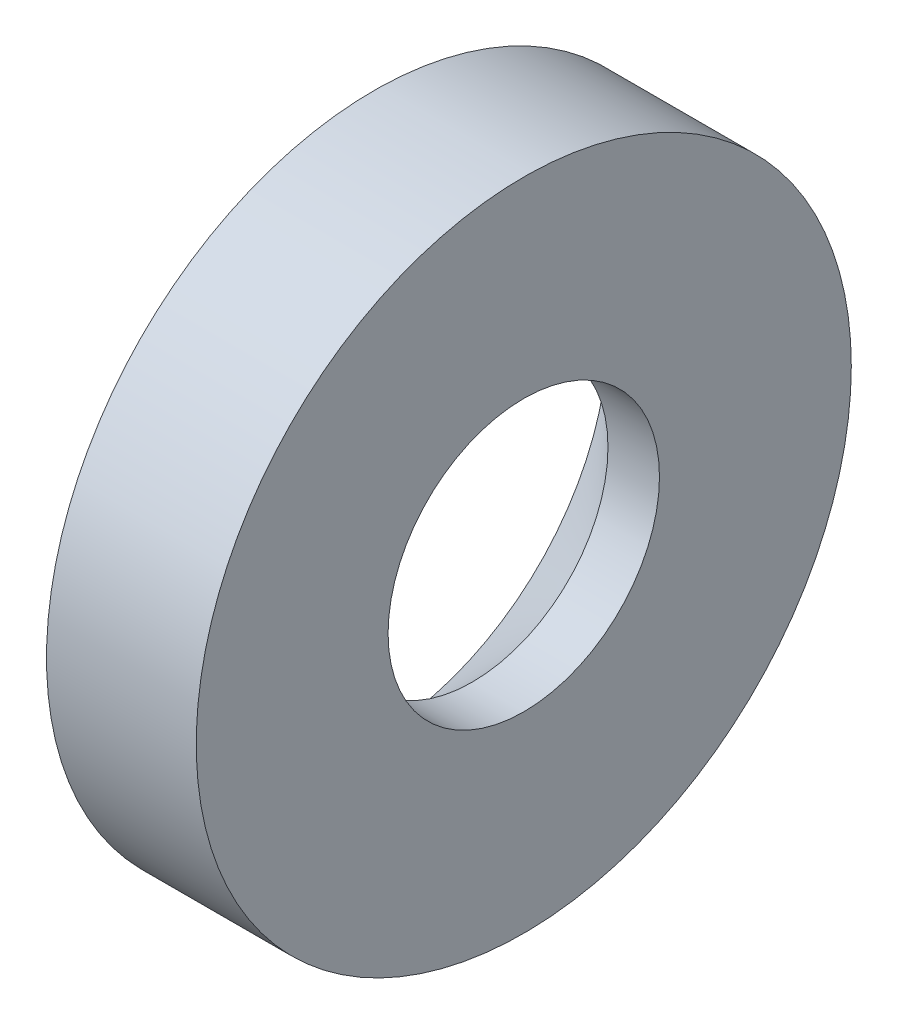
SolidWorks part; units mm, degrees
ref_plane "Front Plane" through (0, 0, 0) normal (0, 0, 1) x (1, 0, 0)
ref_plane "Top Plane" through (0, 0, 0) normal (0, 1, 0) x (1, 0, 0)
ref_plane "Right Plane" through (0, 0, 0) normal (1, 0, 0) x (0, 0, -1)
sketch "Sketch1" plane through (0, 0, 0) normal (1, 0, 0) x (0, 0, -1)
  circle A0 centre (0, 0) radius 17.5
  dimension "D1" = 35
extrude "Boss-Extrude1" add sketch "Sketch1" along normal mid plane 8
hole_wizard "CSK for M20 SFHCS1" positions "Sketch7" profile "Sketch6" countersink size "M20" standard "ANSI Metric"
sketch "Sketch7" plane through (-4, 0, 0) normal (-1, 0, 0) x (0, 0, 1)
  point P0 (0, 0)
sketch "Sketch6" plane through (-4, 0, 0) normal (0, 1, 0) x (0, 0, 1)
  line L0 (0, 0) -> (0, 35)
  line L1 (0, 35) -> (7.25, 30.6438)
  line L2 (7.25, 30.6438) -> (7.25, 5.25)
  line L3 (7.25, 5.25) -> (12.5, 0)
  line L5 (12.5, 0) -> (0, 0)
  line L6 (-7.25, 5.25) -> (-12.5, 0) construction
  line L10 (0, 35) -> (-7.25, 30.6438) construction
  line L11 (0, -6.35) -> (0, 107.95) construction
  dimension "Hole Dia." = 14.5
  dimension "Hole Depth" = 35
  dimension "Near C'Sink Dia." = 25
  dimension "Near C'Sink Angle" = 90
  dimension "Drill Angle" = 118
